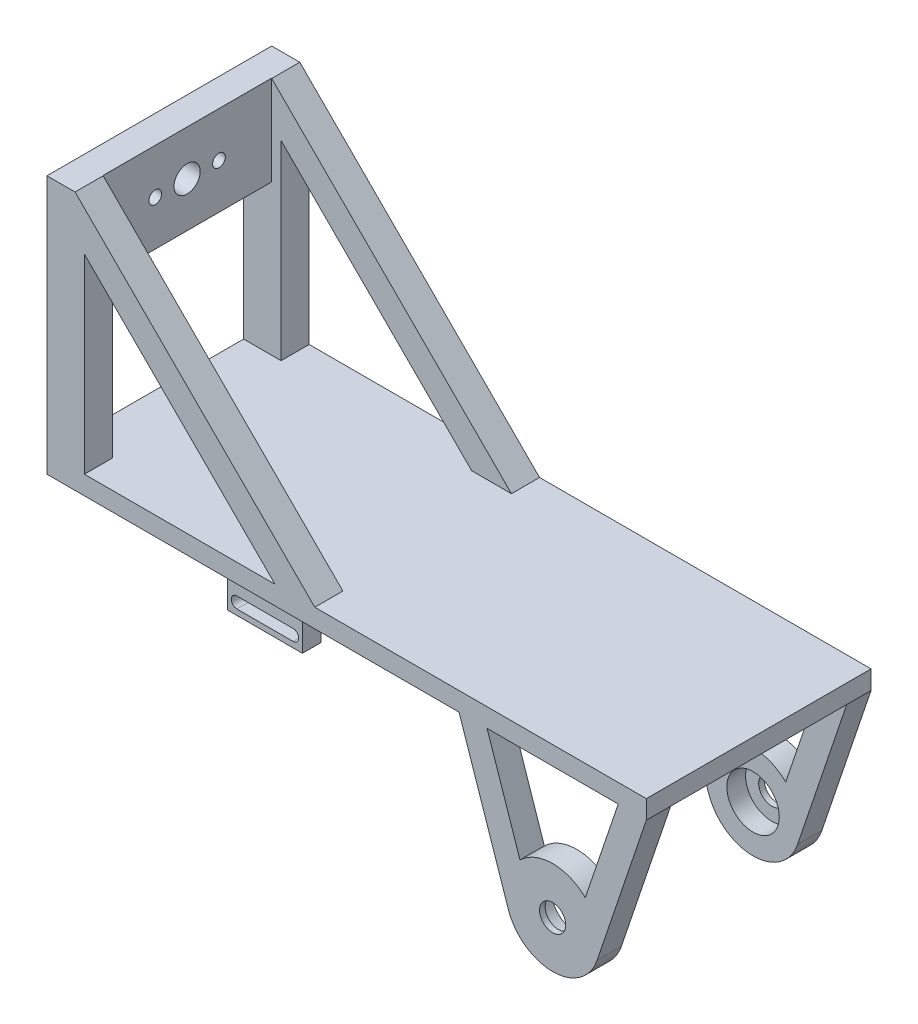
SolidWorks part; units mm, degrees
ref_plane "Front Plane" through (0, 0, 0) normal (0, 0, 1) x (1, 0, 0)
ref_plane "Top Plane" through (0, 0, 0) normal (0, 1, 0) x (1, 0, 0)
ref_plane "Right Plane" through (0, 0, 0) normal (1, 0, 0) x (0, 0, -1)
sketch "Sketch1" plane through (0, 0, 0) normal (0, 1, 0) x (1, 0, 0)
  line L1 (-80, -30) -> (80, -30)
  line L2 (-80, -30) -> (-80, 30)
  line L3 (-80, 30) -> (80, 30)
  line L4 (80, -30) -> (80, 30)
  line L5 (-80, -30) -> (80, 30) construction
  line L6 (-80, 30) -> (80, -30) construction
  point P0 (0, 0)
  dimension "D1" = 160
  dimension "D2" = 60
extrude "Boss-Extrude1" add sketch "Sketch1" along normal blind 5
sketch "Sketch8" plane through (0, 0, 0) normal (0, 0, 1) x (1, 0, 0)
  line L0 (-80, 0) -> (80, 0) construction
  line L1 (-47.5, 0) -> (-27.5, 0)
  line L2 (-47.5, 0) -> (-47.5, -23)
  line L3 (-47.5, -23) -> (-27.5, -23)
  line L4 (-27.5, 0) -> (-27.5, -23)
  line L5 (-80, 5) -> (-80, 0) construction
  line L6 (-45, -18.5) -> (-30, -18.5)
  line L7 (-45, -21.5) -> (-30, -21.5)
  line L8 (-45, -0.9) -> (-30, -0.9)
  line L9 (-30, -3.9) -> (-45, -3.9)
  arc A0 (-45, -18.5) -> (-45, -21.5) centre (-45, -20) ccw
  arc A1 (-30, -21.5) -> (-30, -18.5) centre (-30, -20) ccw
  arc A2 (-45, -0.9) -> (-45, -3.9) centre (-45, -2.4) ccw
  arc A4 (-30, -3.9) -> (-30, -0.9) centre (-30, -2.4) ccw
  point P9 (0, 0)
  point P11 (0, 0)
  point P17 (0, 0)
  dimension "D4" = 2.5
  dimension "D5" = 2.5
  dimension "D6" = 2.4
  dimension "D7" = 17.6
  dimension "D1" = 32.5
  dimension "D2" = 3
  dimension "D3" = 20
extrude "Boss-Extrude3" add sketch "Sketch8" along normal blind 14.3 and the other way blind 14.3
sketch "Sketch9" plane through (-47.5, 0, 0) normal (-1, 0, 0) x (0, 0, 1)
  line L0 (-14.3, -23) -> (14.3, -23) construction
  line L1 (-9.3, -23) -> (9.3, -23)
  line L2 (-9.3, -23) -> (-9.3, -13.4)
  line L3 (-9.3, 0) -> (9.3, 0)
  line L4 (9.3, -23) -> (9.3, 0)
  line L5 (-14.3, 0) -> (14.3, 0) construction
  line L6 (14.3, 0) -> (14.3, -23) construction
  line L7 (-14.3, 0) -> (-14.3, -23) construction
  line L8 (-9.3, -9.4) -> (-9.3, 0)
  line L9 (-9.3, -9.4) -> (-11.3, -9.4)
  line L11 (-9.3, -13.4) -> (-11.3, -13.4)
  line L12 (-11.3, -9.4) -> (-11.3, -13.4)
  dimension "D1" = 5
  dimension "D2" = 5
  dimension "D3" = 4
  dimension "D4" = 9.4
  dimension "D5" = 2
extrude "Cut-Extrude1" cut sketch "Sketch9" against normal up to surface (20 mm away) up to face at (-27.5, -11.5, 0)
sketch "Sketch10" plane through (0, 0, 30) normal (0, 0, 1) x (1, 0, 0)
  line L0 (-72.5, 69) -> (-8.5, 5)
  line L1 (-80, 5) -> (-72.5, 5)
  line L2 (-80, 5) -> (-80, 69)
  line L3 (-80, 69) -> (-72.5, 69)
  line L5 (-80, 5) -> (80, 5) construction
  line L6 (-8.5, 5) -> (-19.1066, 5)
  line L7 (-70, 55.8934) -> (-19.1066, 5)
  line L9 (-70, 5) -> (-70, 55.8934)
  line L10 (-70, 5) -> (-72.5, 5)
  dimension "D1" = 64
  dimension "D2" = 7.5
  dimension "D3" = 45
  dimension "D4" = 7.5
  dimension "D5" = 10
extrude "Boss-Extrude4" add sketch "Sketch10" against normal up to surface (60 mm away) up to face at (0, 2.5, -30)
sketch "Sketch11" plane through (-80, 0, 0) normal (-1, 0, 0) x (0, 0, 1)
  line L1 (-30, 69) -> (-30, 0) construction
  line L2 (-22.5, 45) -> (22.5, 45)
  line L3 (-22.5, 45) -> (-22.5, 5)
  line L4 (-22.5, 5) -> (22.5, 5)
  line L5 (22.5, 45) -> (22.5, 5)
  line L6 (30, 69) -> (30, 0) construction
  line L7 (-30, 0) -> (30, 0) construction
  dimension "D1" = 7.5
  dimension "D2" = 7.5
  dimension "D3" = 5
  dimension "D4" = 40
extrude "Cut-Extrude2" cut sketch "Sketch11" against normal up to vertex
sketch "Sketch12" plane through (0, 69, 0) normal (0, 1, 0) x (1, 0, 0)
  line L0 (-48.5, 22.5) -> (-48.5, -22.5)
  line L1 (-48.5, 22.5) -> (-72.5826, 22.5)
  line L2 (-48.5, -22.5) -> (-72.5826, -22.5)
  line L3 (-72.5826, 22.5) -> (-72.5826, -22.5)
extrude "Cut-Extrude3" cut sketch "Sketch12" against normal up to vertex (24 mm away)
sketch "Sketch13" plane through (-80, 0, 0) normal (-1, 0, 0) x (0, 0, 1)
  line L0 (-30, 69) -> (30, 69) construction
  circle A0 centre (0, 57) radius 3.5
  circle A1 centre (-8.5, 57) radius 1.7
  circle A2 centre (8.5, 57) radius 1.7
  dimension "D1" = 12
  dimension "D2" = 8.5
  dimension "D4" = 17
extrude "Cut-Extrude4" cut sketch "Sketch13" against normal up to surface (7.4174 mm away) up to face at (-72.5826, 57, 0)
sketch "Sketch14" plane through (0, 0, 30) normal (0, 0, 1) x (1, 0, 0)
  line L0 (80, 5) -> (80, 0) construction
  line L1 (-80, 0) -> (80, 0) construction
  line L2 (80, 0) -> (66.8441, -38.9958)
  line L3 (30, 0) -> (43.1559, -38.9958)
  line L4 (72.5, 0) -> (63.7152, -26.0393)
  line L5 (37.5, 0) -> (46.2848, -26.0393)
  line L6 (30, 0) -> (37.5, 0)
  line L7 (72.5, 0) -> (80, 0)
  circle A1 centre (55, -35) radius 3.5
  arc A2 (63.7152, -26.0393) -> (46.2848, -26.0393) centre (55, -35) ccw
  arc A3 (43.1559, -38.9958) -> (66.8441, -38.9958) centre (55, -35) ccw
  dimension "D1" = 25
  dimension "D3" = 25
  dimension "D2" = 35
  dimension "D4" = 0
  dimension "D5" = 7.5
  dimension "D6" = 0
  dimension "D7" = 7.5
extrude "Boss-Extrude5" add sketch "Sketch14" against normal up to surface (60 mm away) up to face at (-53.0355, 21.9645, -30)
sketch "Sketch16" plane through (80, 0, 0) normal (1, 0, 0) x (0, 0, -1)
  line L0 (-30, 0) -> (30, 0) construction
  line L1 (-23.5, 0) -> (23.5, 0)
  line L2 (-23.5, 0) -> (-23.5, -47.8989)
  line L3 (23.5, 0) -> (23.5, -47.8989)
  line L4 (-23.5, -47.8989) -> (23.5, -47.8989)
  line L7 (-30, -38.9958) -> (-30, 0) construction
  line L8 (30, 0) -> (30, -38.9958) construction
  dimension "D1" = 6.5
  dimension "D2" = 6.5
extrude "Cut-Extrude6" cut sketch "Sketch16" against normal up to vertex (107.5 mm away)
sketch "Sketch17" plane through (0, 0, 0) normal (0, 0, 1) x (1, 0, 0)
  circle A1 centre (55, -35) radius 7
extrude "Cut-Extrude7" cut sketch "Sketch17" against normal offset from surface 5 and the other way offset from surface (28.5 mm away) 5 up to face at (55, -16.8794, -23.5) offset beyond the face yes other way up to face at (55, -16.8794, 23.5)
